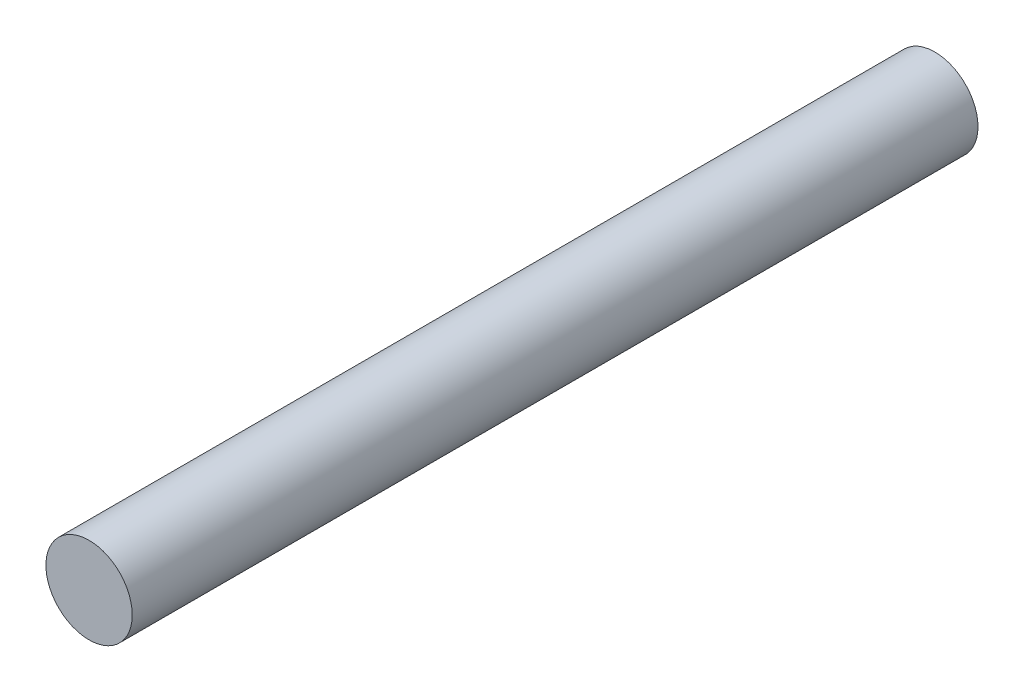
SolidWorks part; units mm, degrees
ref_plane "前视基准面" through (0, 0, 0) normal (0, 0, 1) x (1, 0, 0)
ref_plane "上视基准面" through (0, 0, 0) normal (0, 1, 0) x (1, 0, 0)
ref_plane "右视基准面" through (0, 0, 0) normal (1, 0, 0) x (0, 0, -1)
sketch "草图1" plane through (0, 0, 0) normal (0, 0, 1) x (1, 0, 0)
  circle A0 centre (0, 0) radius 5
  dimension "D1" = 10
extrude "凸台-拉伸1" add sketch "草图1" along normal blind 98
